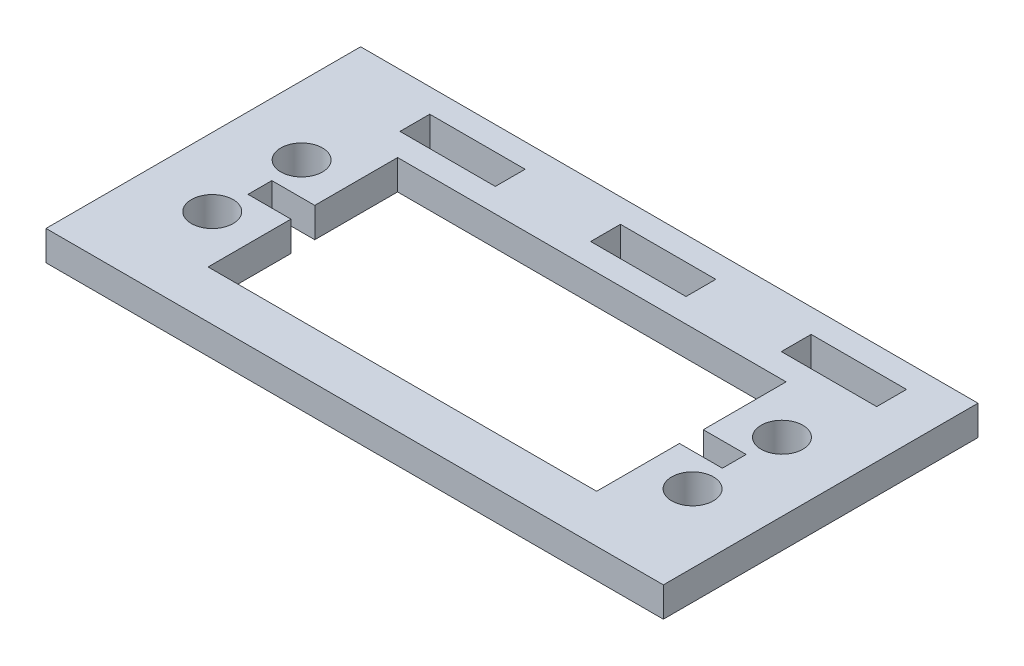
SolidWorks part; units mm, degrees
ref_plane "Front Plane" through (0, 0, 0) normal (0, 0, 1) x (1, 0, 0)
ref_plane "Top Plane" through (0, 0, 0) normal (0, 1, 0) x (1, 0, 0)
ref_plane "Right Plane" through (0, 0, 0) normal (1, 0, 0) x (0, 0, -1)
sketch "Sketch1" plane through (0, 0, 0) normal (0, 1, 0) x (1, 0, 0)
  line L0 (27.813, -10.0965) -> (32.893, -10.0965) construction
  line L1 (32.893, 18.3515) -> (-32.893, 18.3515)
  line L2 (32.893, 18.3515) -> (32.893, -15.1765)
  line L3 (32.893, -15.1765) -> (-32.893, -15.1765)
  line L4 (-32.893, 18.3515) -> (-32.893, -15.1765)
  line L5 (27.813, -10.0965) -> (27.813, -15.1765) construction
  line L6 (-27.813, -10.0965) -> (-32.893, -10.0965) construction
  line L7 (-27.813, 10.0965) -> (27.813, 10.0965) construction
  line L8 (-27.813, 10.0965) -> (-27.813, -10.0965) construction
  line L9 (-27.813, -10.0965) -> (27.813, -10.0965) construction
  line L10 (27.813, 10.0965) -> (27.813, -10.0965) construction
  line L11 (-27.813, 10.0965) -> (27.813, -10.0965) construction
  line L12 (-27.813, -10.0965) -> (27.813, 10.0965) construction
  line L13 (27.813, 15.8115) -> (27.813, 18.3515) construction
  line L14 (27.813, 15.8115) -> (17.653, 15.8115)
  line L15 (27.813, 15.8115) -> (27.813, 12.6365)
  line L16 (27.813, 12.6365) -> (17.653, 12.6365)
  line L17 (17.653, 15.8115) -> (17.653, 12.6365)
  line L18 (27.813, 15.8115) -> (17.653, 12.6365) construction
  line L19 (27.813, 12.6365) -> (17.653, 15.8115) construction
  line L20 (27.813, 12.6365) -> (27.813, 10.0965) construction
  line L21 (7.493, 15.8115) -> (7.493, 12.6365)
  line L22 (7.493, 15.8115) -> (-2.667, 15.8115)
  line L23 (7.493, 12.6365) -> (-2.667, 12.6365)
  line L24 (-2.667, 15.8115) -> (-2.667, 12.6365)
  line L25 (-12.827, 15.8115) -> (-12.827, 12.6365)
  line L26 (-12.827, 15.8115) -> (-22.987, 15.8115)
  line L27 (-12.827, 12.6365) -> (-22.987, 12.6365)
  line L28 (-22.987, 15.8115) -> (-22.987, 12.6365)
  line L29 (-20.701, 0) -> (-27.813, 0) construction
  line L30 (-20.701, -10.0965) -> (20.701, -10.0965)
  line L31 (-20.701, -10.0965) -> (-20.701, 10.0965) construction
  line L32 (-20.701, 10.0965) -> (20.701, 10.0965)
  line L33 (20.701, -10.0965) -> (20.701, 10.0965) construction
  line L34 (-20.701, -10.0965) -> (20.701, 10.0965) construction
  line L35 (-20.701, 10.0965) -> (20.701, -10.0965) construction
  line L36 (20.701, 0) -> (27.813, 0) construction
  line L37 (-27.813, 9.525) -> (27.813, 9.525) construction
  line L38 (-27.813, -9.525) -> (27.813, -9.525) construction
  line L39 (-25.5905, 9.525) -> (-25.5905, 0) construction
  line L40 (-25.5905, 0) -> (-25.5905, -9.525) construction
  line L41 (-25.5905, 4.7625) -> (25.5905, 4.7625) construction
  line L42 (-25.5905, -4.7625) -> (25.5905, -4.7625) construction
  line L43 (0, 0) -> (0, 6.8647) construction
  line L44 (20.701, 1.27) -> (25.273, 1.27)
  line L46 (20.701, -1.27) -> (25.273, -1.27)
  line L47 (25.273, 1.27) -> (25.273, -1.27)
  line L48 (-20.701, 1.27) -> (-25.273, 1.27)
  line L49 (-25.273, 1.27) -> (-25.273, -1.27)
  line L50 (-20.701, -1.27) -> (-25.273, -1.27)
  line L51 (-20.701, 10.0965) -> (-20.701, 1.27)
  line L52 (-20.701, -1.27) -> (-20.701, -10.0965)
  line L53 (20.701, -10.0965) -> (20.701, -1.27)
  line L54 (20.701, 1.27) -> (20.701, 10.0965)
  circle A0 centre (-25.5905, 4.7625) radius 2.2225
  circle A1 centre (-25.5905, -4.7625) radius 2.2225
  circle A2 centre (25.5905, 4.7625) radius 2.2225
  circle A3 centre (25.5905, -4.7625) radius 2.2225
  point P0 (0, 0)
  point P4 (22.733, 14.224)
  point P6 (0, 0)
  point P20 (0, 0)
  dimension "D9" = 4.445
  dimension "D1" = 20.193
  dimension "D2" = 55.626
  dimension "D3" = 5.08
  dimension "D4" = 3.175
  dimension "D5" = 10.16
  dimension "D6" = 2.54
  dimension "D7" = 3
  dimension "D8" = 7.112
  dimension "D10" = 19.05
  dimension "D11" = 4.572
  dimension "D12" = 2.54
extrude "Boss-Extrude2" add sketch "Sketch1" along normal blind 3.175 contours L1 L4 L3 L2 A3 A2 A1 A0 L28 L26 L25 L27 L24 L22 L21 L23 L17 L14 L15 L16 L31 L50 L49 L48 L32 L33 L44 L47 L46 L30
sketch "Sketch2" plane through (0, 0, 0) normal (0, 1, 0) x (1, 0, 0)
  line L30 (32.9692, -15.2527) -> (32.9692, 18.4277)
  line L31 (-32.9692, -15.2527) -> (32.9692, -15.2527)
  line L32 (-32.9692, 18.4277) -> (-32.9692, -15.2527)
  line L33 (32.9692, 18.4277) -> (-32.9692, 18.4277)
  line L34 (32.9692, -15.2527) -> (32.9692, 18.4277)
  line L35 (-32.9692, -15.2527) -> (32.9692, -15.2527)
  line L36 (-32.9692, 18.4277) -> (-32.9692, -15.2527)
  line L37 (32.9692, 18.4277) -> (-32.9692, 18.4277)
  line L48 (-12.9032, 12.7127) -> (-12.9032, 15.7353)
  line L49 (-12.9032, 15.7353) -> (-22.9108, 15.7353)
  line L50 (-22.9108, 15.7353) -> (-22.9108, 12.7127)
  line L51 (-22.9108, 12.7127) -> (-12.9032, 12.7127)
  line L52 (-12.9032, 12.7127) -> (-12.9032, 15.7353)
  line L53 (-12.9032, 15.7353) -> (-22.9108, 15.7353)
  line L54 (-22.9108, 15.7353) -> (-22.9108, 12.7127)
  line L55 (-22.9108, 12.7127) -> (-12.9032, 12.7127)
  line L60 (7.4168, 12.7127) -> (7.4168, 15.7353)
  line L61 (7.4168, 15.7353) -> (-2.5908, 15.7353)
  line L62 (-2.5908, 15.7353) -> (-2.5908, 12.7127)
  line L63 (-2.5908, 12.7127) -> (7.4168, 12.7127)
  line L64 (7.4168, 12.7127) -> (7.4168, 15.7353)
  line L65 (7.4168, 15.7353) -> (-2.5908, 15.7353)
  line L66 (-2.5908, 15.7353) -> (-2.5908, 12.7127)
  line L67 (-2.5908, 12.7127) -> (7.4168, 12.7127)
  line L72 (27.7368, 12.7127) -> (27.7368, 15.7353)
  line L73 (27.7368, 15.7353) -> (17.7292, 15.7353)
  line L74 (17.7292, 15.7353) -> (17.7292, 12.7127)
  line L75 (17.7292, 12.7127) -> (27.7368, 12.7127)
  line L76 (27.7368, 12.7127) -> (27.7368, 15.7353)
  line L77 (27.7368, 15.7353) -> (17.7292, 15.7353)
  line L78 (17.7292, 15.7353) -> (17.7292, 12.7127)
  line L79 (17.7292, 12.7127) -> (27.7368, 12.7127)
  line L167 (-20.6248, 1.1938) -> (-25.1968, 1.1938)
  line L168 (-25.1968, 1.1938) -> (-25.1968, -1.1938)
  line L169 (-25.1968, -1.1938) -> (-20.6248, -1.1938)
  line L170 (-20.6248, -1.1938) -> (-20.6248, -10.0203)
  line L171 (-20.6248, -10.0203) -> (20.6248, -10.0203)
  line L172 (20.6248, -10.0203) -> (20.6248, -1.1938)
  line L173 (20.6248, -1.1938) -> (25.1968, -1.1938)
  line L174 (25.1968, -1.1938) -> (25.1968, 1.1938)
  line L175 (25.1968, 1.1938) -> (20.6248, 1.1938)
  line L176 (20.6248, 1.1938) -> (20.6248, 10.0203)
  line L177 (20.6248, 10.0203) -> (-20.6248, 10.0203)
  line L178 (-20.6248, 10.0203) -> (-20.6248, 1.1938)
  line L179 (-20.6248, 1.1938) -> (-25.1968, 1.1938)
  line L180 (-25.1968, 1.1938) -> (-25.1968, -1.1938)
  line L181 (-25.1968, -1.1938) -> (-20.6248, -1.1938)
  line L182 (-20.6248, -1.1938) -> (-20.6248, -10.0203)
  line L183 (-20.6248, -10.0203) -> (20.6248, -10.0203)
  line L184 (20.6248, -10.0203) -> (20.6248, -1.1938)
  line L185 (20.6248, -1.1938) -> (25.1968, -1.1938)
  line L186 (25.1968, -1.1938) -> (25.1968, 1.1938)
  line L187 (25.1968, 1.1938) -> (20.6248, 1.1938)
  line L188 (20.6248, 1.1938) -> (20.6248, 10.0203)
  line L189 (20.6248, 10.0203) -> (-20.6248, 10.0203)
  line L190 (-20.6248, 10.0203) -> (-20.6248, 1.1938)
  circle A47 centre (-25.5905, 4.7625) radius 2.1463
  circle A48 centre (-25.5905, 4.7625) radius 2.1463
  circle A50 centre (-25.5905, -4.7625) radius 2.1463
  circle A51 centre (-25.5905, -4.7625) radius 2.1463
  circle A56 centre (25.5905, 4.7625) radius 2.1463
  circle A57 centre (25.5905, 4.7625) radius 2.1463
  circle A59 centre (25.5905, -4.7625) radius 2.1463
  circle A60 centre (25.5905, -4.7625) radius 2.1463
  dimension "D1" = 0.0762
  dimension "D2" = 0.0762
  dimension "D3" = 0.0762
  dimension "D4" = 0.0762
  dimension "D5" = 0.0762
  dimension "D6" = 0.0762
  dimension "D7" = 0.0762
  dimension "D8" = 0.0762
  dimension "D10" = 0.0762
